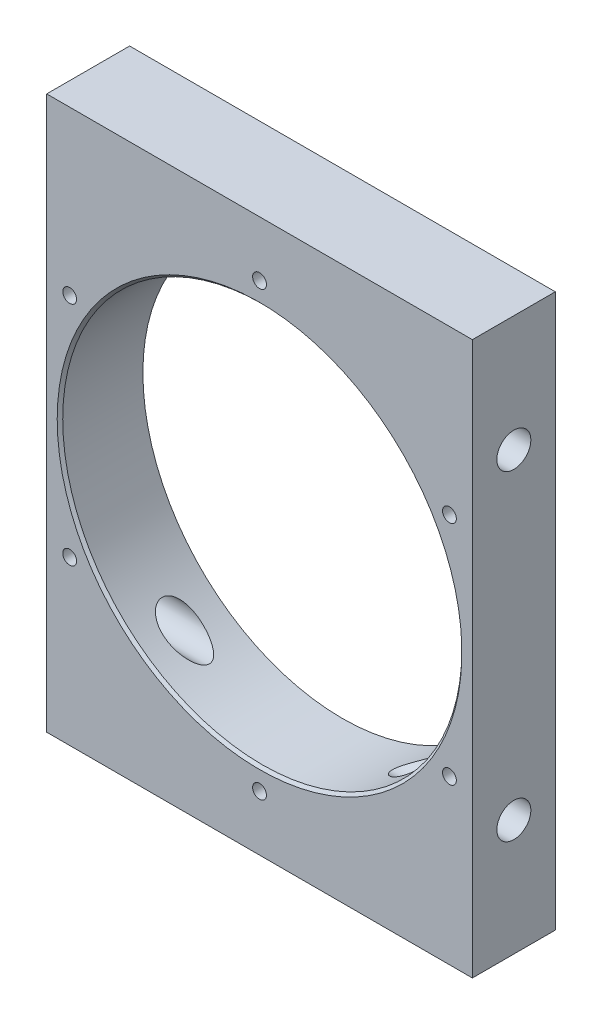
SolidWorks part; units mm, degrees
ref_plane "Ebene vorne" through (0, 0, 0) normal (0, 0, 1) x (1, 0, 0)
ref_plane "Ebene oben" through (0, 0, 0) normal (0, 1, 0) x (1, 0, 0)
ref_plane "Ebene rechts" through (0, 0, 0) normal (1, 0, 0) x (0, 0, -1)
sketch "Skizze1" plane through (0, 0, 0) normal (0, 0, 1) x (1, 0, 0)
  line L1 (-38.5, -50) -> (38.5, -50)
  line L2 (-38.5, -50) -> (-38.5, 50)
  line L3 (-38.5, 50) -> (38.5, 50)
  line L4 (38.5, -50) -> (38.5, 50)
  line L5 (-38.5, -50) -> (38.5, 50) construction
  line L6 (-38.5, 50) -> (38.5, -50) construction
  point P0 (0, 0)
  dimension "D1" = 77
  dimension "D2" = 100
extrude "Aufsatz-Linear austragen1" add sketch "Skizze1" along normal mid plane 15
sketch "Skizze2" plane through (0, 0, 7.5) normal (0, 0, 1) x (1, 0, 0)
  circle A0 centre (0, 0) radius 36.1
  dimension "D1" = 72.2
extrude "Schnitt-Linear austragen1" cut sketch "Skizze2" against normal through all
sketch "Skizze3" plane through (38.5, 0, 0) normal (1, 0, 0) x (0, 0, -1)
  line L0 (0, 0) -> (0, -50000) construction
  line L1 (0, 0) -> (26.9663, 0) construction
  circle A0 centre (0, 29) radius 3.075
  circle A1 centre (0, -29) radius 3.075
  dimension "D1" = 6.15
  dimension "D2" = 29
extrude "Schnitt-Linear austragen2" cut sketch "Skizze3" against normal through all
chamfer "Fase1" distance 0.5 angle 45 1 edges at (36.1, 0, 7.5)
hole_wizard "M3 Gewindebohrung1" positions "Skizze4" profile "Skizze5" tap size "M3" standard "ISO" end condition through all
sketch "Skizze4" plane through (0, 0, 7.5) normal (0, 0, 1) x (1, 0, 0)
  line L0 (0, 0) -> (50000, 0) construction
  line L1 (0, 0) -> (0, -50000) construction
  circle A0 centre (0, 0) radius 40 construction
  point P6 (0, 40)
  point P8 (0, -40)
  point P10 (34.3475, -20.5)
  point P22 (34.3475, 20.5)
  point P23 (-34.3475, -20.5)
  point P24 (-34.3475, 20.5)
  dimension "D1" = 80
  dimension "D2" = 20.5
sketch "Skizze5" plane through (-34.3475, 20.5, 7.5) normal (1, 0, 0) x (0, -1, 0)
  line L0 (0, 0) -> (0, 15)
  line L1 (0, 15) -> (1.25, 15)
  line L2 (1.25, 15) -> (1.25, 0)
  line L5 (1.25, 0) -> (0, 0)
  line L11 (0, -6.35) -> (0, 107.95) construction
  dimension "Bohrerdurchmesser" = 2.5
  dimension "Bohrungstiefe" = 15
